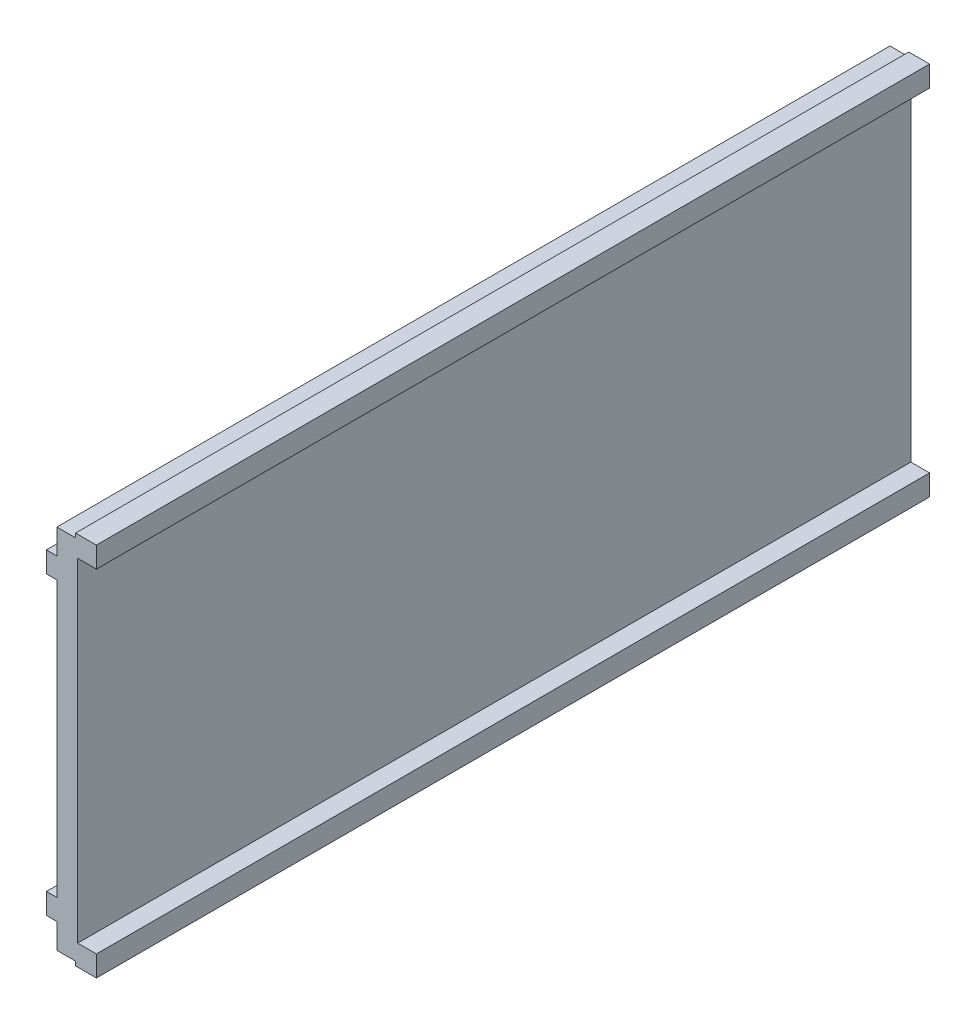
SolidWorks part; units mm, degrees
ref_plane "Front Plane" through (0, 0, 0) normal (0, 0, 1) x (1, 0, 0)
ref_plane "Top Plane" through (0, 0, 0) normal (0, 1, 0) x (1, 0, 0)
ref_plane "Right Plane" through (0, 0, 0) normal (1, 0, 0) x (0, 0, -1)
sketch "Sketch1" plane through (0, 0, 0) normal (0, 0, 1) x (1, 0, 0)
  line L0 (-46.0419, -5.2089) -> (-46.0419, -6.2089)
  line L1 (-46.0419, -6.2089) -> (-50.5419, -6.2089)
  line L2 (-50.5419, -6.2089) -> (-50.5419, -12.2089)
  line L3 (-41.0419, -10.2089) -> (-41.0419, -5.2089)
  line L4 (-41.0419, -5.2089) -> (-46.0419, -5.2089)
  line L5 (-71.3009, -50.2089) -> (-50.5419, -50.2089) construction
  line L6 (-53.0419, -12.2089) -> (-50.5419, -12.2089)
  line L7 (-53.0419, -12.2089) -> (-53.0419, -17.2089)
  line L8 (-53.0419, -17.2089) -> (-50.5419, -17.2089)
  line L11 (-50.5419, -17.2089) -> (-50.5419, -83.2089)
  line L21 (-45.5419, -50.2089) -> (-36.3492, -50.2089) construction
  line L23 (-45.5419, -10.2089) -> (-41.0419, -10.2089)
  line L24 (-45.5419, -10.2089) -> (-45.5419, -90.2089)
  line L25 (-45.5419, -90.2089) -> (-41.0419, -90.2089)
  line L26 (-53.0419, -83.2089) -> (-50.5419, -83.2089)
  line L27 (-53.0419, -88.2089) -> (-53.0419, -83.2089)
  line L28 (-53.0419, -88.2089) -> (-50.5419, -88.2089)
  line L29 (-41.0419, -95.2089) -> (-46.0419, -95.2089)
  line L30 (-41.0419, -90.2089) -> (-41.0419, -95.2089)
  line L31 (-50.5419, -94.2089) -> (-50.5419, -88.2089)
  line L32 (-46.0419, -94.2089) -> (-50.5419, -94.2089)
  line L33 (-46.0419, -95.2089) -> (-46.0419, -94.2089)
  dimension "D1" = 5
  dimension "D2" = 5
  dimension "D3" = 5
  dimension "D4" = 2.5
  dimension "D5" = 1
  dimension "D8" = 45
  dimension "D9" = 5
extrude "Boss-Extrude1" add sketch "Sketch1" along normal blind 200
